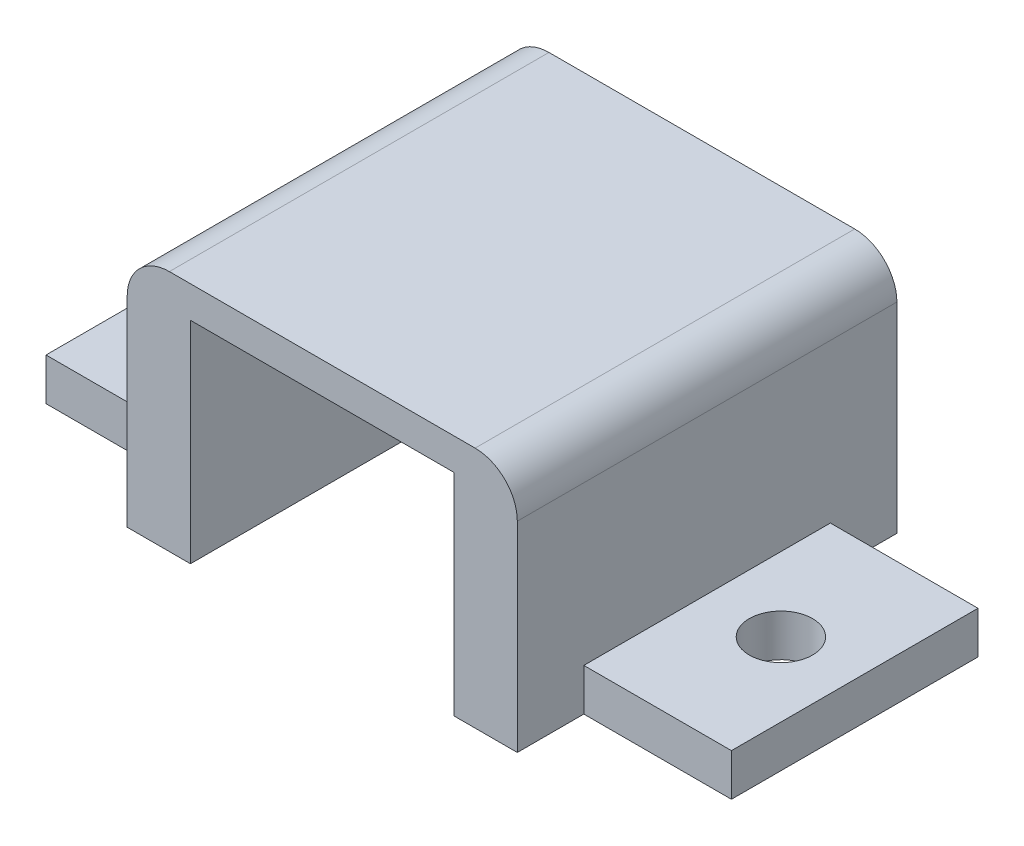
SolidWorks part; units mm, degrees
ref_plane "Front Plane" through (0, 0, 0) normal (0, 0, 1) x (1, 0, 0)
ref_plane "Top Plane" through (0, 0, 0) normal (0, 1, 0) x (1, 0, 0)
ref_plane "Right Plane" through (0, 0, 0) normal (1, 0, 0) x (0, 0, -1)
sketch "Sketch2" plane through (0, 0, 0) normal (0, 0, 1) x (1, 0, 0)
  line L0 (-9.25, 0) -> (-9.25, 9.5)
  line L1 (-7.25, 11.5) -> (7.25, 11.5)
  line L2 (9.25, 9.5) -> (9.25, 0)
  line L3 (9.25, 0) -> (6.25, 0)
  line L4 (6.25, 0) -> (6.25, 10)
  line L5 (6.25, 10) -> (-6.25, 10)
  line L6 (-6.25, 10) -> (-6.25, 0)
  line L7 (-6.25, 0) -> (-9.25, 0)
  arc A0 (7.25, 11.5) -> (9.25, 9.5) centre (7.25, 9.5) cw
  arc A1 (-9.25, 9.5) -> (-7.25, 11.5) centre (-7.25, 9.5) cw
  point P13 (-9.25, 11.5)
  point P14 (0, 10)
  dimension "D3" = 2
  dimension "D1" = 12.5
  dimension "D2" = 11.5
  dimension "D4" = 10
  dimension "D5" = 3
extrude "Boss-Extrude1" add sketch "Sketch2" along normal blind 18
sketch "Sketch3" plane through (9.25, 0, 0) normal (1, 0, 0) x (0, 0, -1)
  line L0 (-18, 0) -> (0, 0) construction
  line L1 (-14.8461, 0) -> (-3.1539, 0)
  line L2 (-14.8461, 0) -> (-14.8461, 2)
  line L3 (-14.8461, 2) -> (-3.1539, 2)
  line L4 (-3.1539, 0) -> (-3.1539, 2)
  line L5 (-9, 2) -> (-9, 0) construction
  line L6 (-9, 9.5) -> (-9, 0) construction
  line L7 (-18, 9.5) -> (0, 9.5) construction
  line L8 (-18, 0) -> (-18, 9.5) construction
  dimension "D1" = 2
  dimension "D2" = 3.1539
extrude "Boss-Extrude2" add sketch "Sketch3" along normal blind 7
sketch "Sketch4" plane through (-9.25, 0, 0) normal (-1, 0, 0) x (0, 0, 1)
  line L0 (18, 0) -> (0, 0) construction
  line L1 (3.15, 0) -> (14.85, 0)
  line L2 (3.15, 0) -> (3.15, 2)
  line L3 (3.15, 2) -> (14.85, 2)
  line L4 (14.85, 0) -> (14.85, 2)
  line L5 (0, 9.5) -> (0, 0) construction
  line L6 (18, 9.5) -> (18, 0) construction
  dimension "D1" = 3.15
  dimension "D2" = 2
  dimension "D3" = 3.15
extrude "Boss-Extrude3" add sketch "Sketch4" along normal blind 7
sketch "Sketch5" plane through (0, 0, 0) normal (0, -1, 0) x (1, 0, 0)
  line L0 (-9.25, 14.85) -> (-16.25, 3.15) construction
  line L1 (9.25, 14.8461) -> (16.25, 3.1539) construction
  line L2 (16.25, 14.8461) -> (9.25, 14.8461) construction
  line L3 (9.25, 18) -> (9.25, 14.8461) construction
  point P11 (-12.75, 9)
  point P12 (12.75, 9)
hole_wizard "Ø3.0mm Dowel Hole1" positions "Sketch5" profile "Sketch6" hole size "Ø3.0" standard "ANSI Metric"
sketch "Sketch6" plane through (12.75, 0, 9) normal (1, 0, 0) x (0, 0, -1)
  line L0 (0, 0) -> (0, 12.9013)
  line L1 (0, 12.9013) -> (1.5, 12)
  line L2 (1.5, 12) -> (1.5, 0)
  line L5 (1.5, 0) -> (0, 0)
  line L10 (0, 12.9013) -> (-1.5, 12) construction
  line L11 (0, -6.35) -> (0, 107.95) construction
  dimension "Hole Dia." = 3
  dimension "Hole Depth" = 12
  dimension "Drill Angle" = 118
